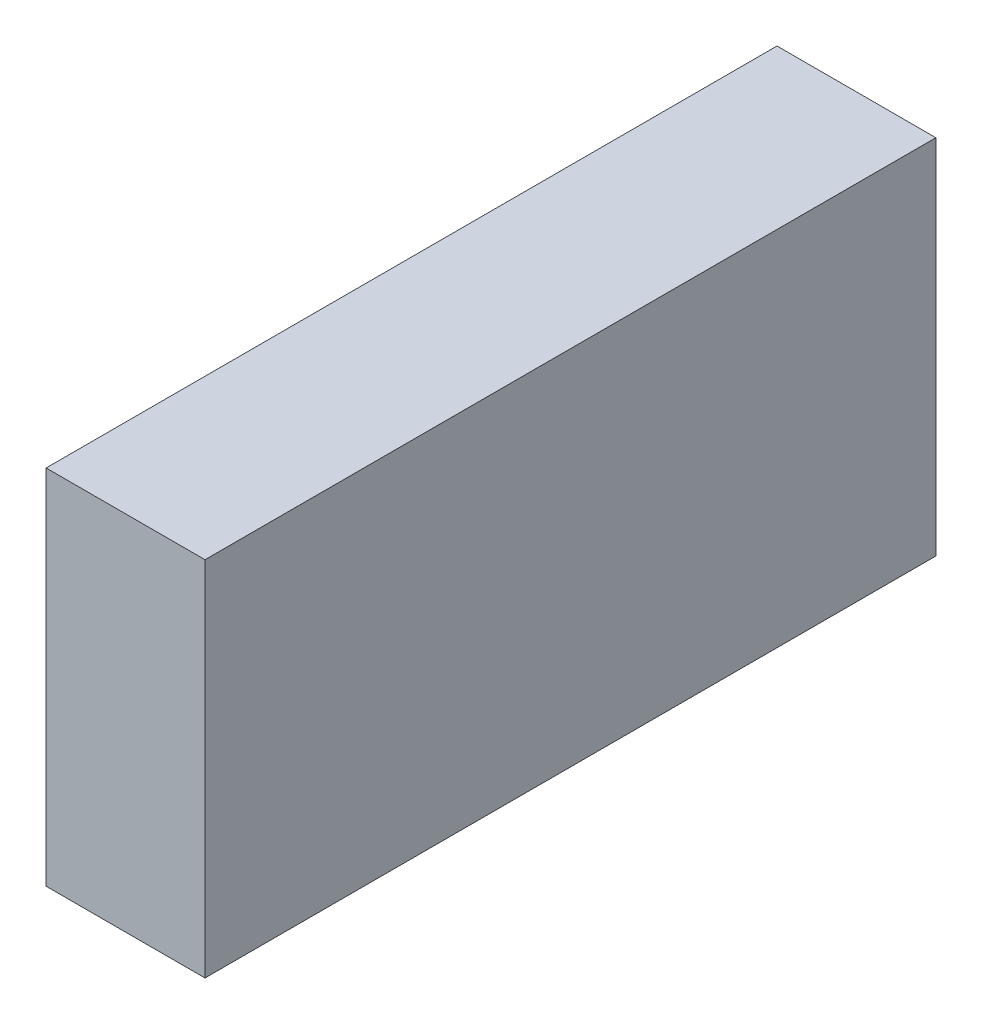
SolidWorks part; units mm, degrees
material "Porcelana cerâmica"
ref_plane "Plano frontal" through (0, 0, 0) normal (0, 0, 1) x (1, 0, 0)
ref_plane "Plano superior" through (0, 0, 0) normal (0, 1, 0) x (1, 0, 0)
ref_plane "Plano direito" through (0, 0, 0) normal (1, 0, 0) x (0, 0, -1)
sketch "Esboço1" plane through (0, 0, 0) normal (0, 0, 1) x (1, 0, 0)
  line L1 (0, 0) -> (50, 0)
  line L2 (0, 0) -> (0, 114)
  line L3 (0, 114) -> (50, 114)
  line L4 (50, 0) -> (50, 114)
  dimension "D1" = 114
  dimension "D2" = 50
extrude "Ressalto-extrusão1" add sketch "Esboço1" along normal blind 230
